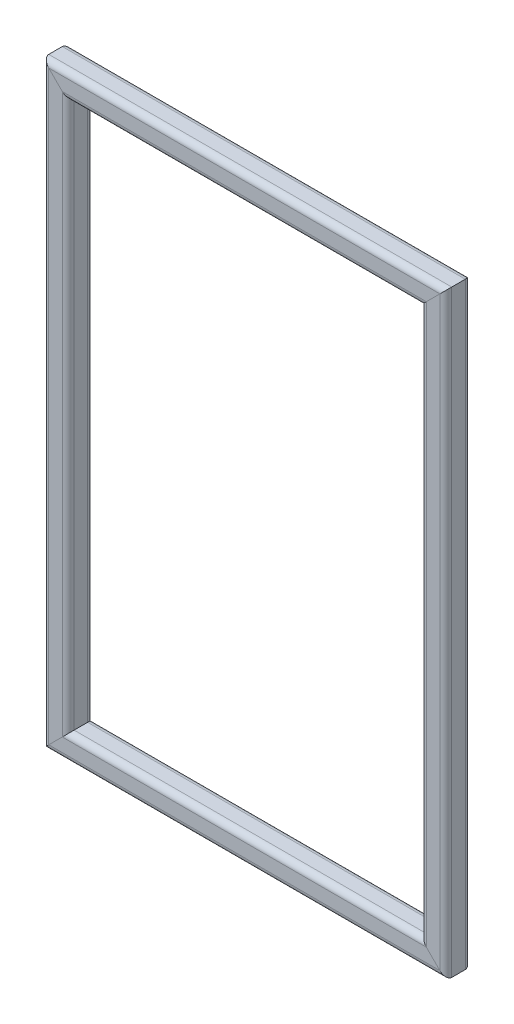
SolidWorks part; units mm, degrees
ref_plane "前视基准面" through (0, 0, 0) normal (0, 0, 1) x (1, 0, 0)
ref_plane "上视基准面" through (0, 0, 0) normal (0, 1, 0) x (1, 0, 0)
ref_plane "右视基准面" through (0, 0, 0) normal (1, 0, 0) x (0, 0, -1)
other "Configuration Table"
sketch "草图1" plane through (0, 0, 0) normal (0, 0, 1) x (1, 0, 0)
  line L1 (-223.25, 338.5) -> (223.25, 338.5)
  line L2 (-223.25, 338.5) -> (-223.25, -338.5)
  line L3 (-223.25, -338.5) -> (223.25, -338.5)
  line L4 (223.25, 338.5) -> (223.25, -338.5)
  line L5 (-223.25, 338.5) -> (223.25, -338.5) construction
  line L6 (-223.25, -338.5) -> (223.25, 338.5) construction
  point P0 (0, 0)
  dimension "D1" = 446.5
  dimension "D2" = 677
other "方管 30 X 30 X 3.5(1)"
ref_plane "基准面1" through (-223.25, 338.5, 0) normal (0, -1, 0) x (1, 0, 0)
sketch "Sketch1" plane through (-223.25, 338.5, 0) normal (0, -1, 0) x (1, 0, 0)
  line L0 (-8, -11.5) -> (8, -11.5)
  line L1 (-11.5, -8) -> (-11.5, 8)
  line L2 (8, 11.5) -> (-8, 11.5)
  line L3 (11.5, 8) -> (11.5, -8)
  line L4 (-8, -15) -> (8, -15)
  line L5 (-15, -8) -> (-15, 8)
  line L6 (8, 15) -> (-8, 15)
  line L7 (15, 8) -> (15, -8)
  arc A0 (15, 8) -> (8, 15) centre (8, 8) ccw
  arc A1 (8, -15) -> (15, -8) centre (8, -8) ccw
  arc A2 (-15, -8) -> (-8, -15) centre (-8, -8) ccw
  arc A3 (-8, 15) -> (-15, 8) centre (-8, 8) ccw
  arc A4 (-8, 11.5) -> (-11.5, 8) centre (-8, 8) ccw
  arc A5 (11.5, 8) -> (8, 11.5) centre (8, 8) ccw
  arc A6 (8, -11.5) -> (11.5, -8) centre (8, -8) ccw
  arc A7 (-11.5, -8) -> (-8, -11.5) centre (-8, -8) ccw
  point P0 (-15, 0)
  point P1 (15, 0)
  point P2 (0, 15)
  point P3 (0, -15)
  point P4 (0, 0)
  point P5 (-15, -15)
  point P6 (15, -15)
  point P7 (15, 15)
  point P8 (-15, 15)
  point P33 (0, 0)
  dimension "D1" = 7
  dimension "Thickness" = 3.5
  dimension "V_leg" = 30
